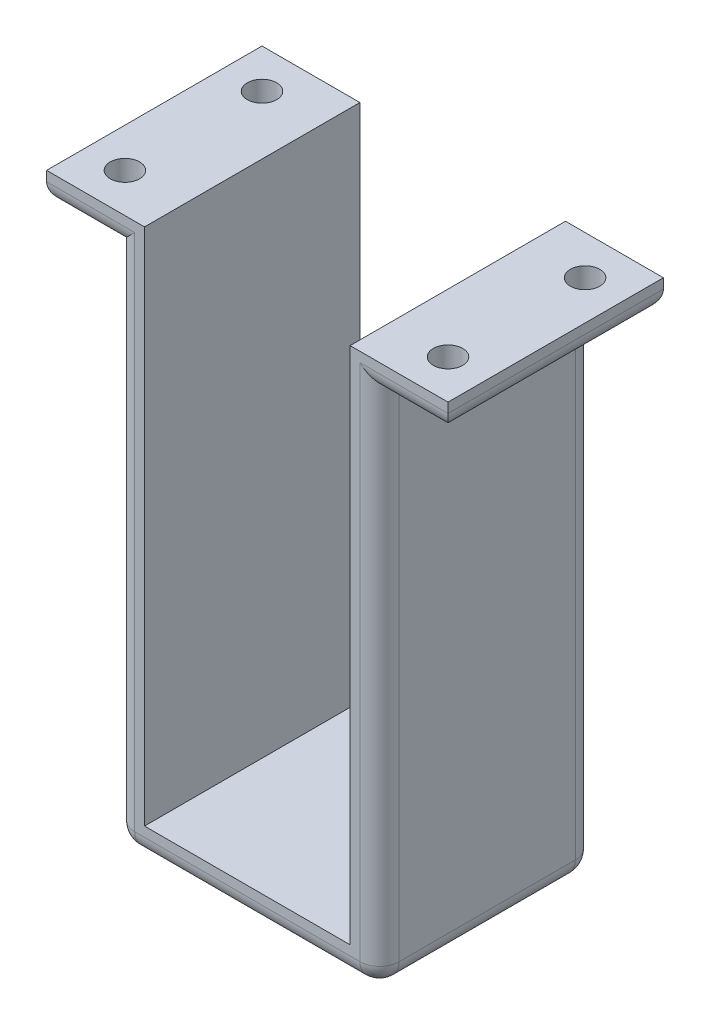
SolidWorks part; units mm, degrees
ref_plane "Alzado" through (0, 0, 0) normal (0, 0, 1) x (1, 0, 0)
ref_plane "Planta" through (0, 0, 0) normal (0, 1, 0) x (1, 0, 0)
ref_plane "Vista lateral" through (0, 0, 0) normal (1, 0, 0) x (0, 0, -1)
sketch "Croquis1" plane through (0, 0, 0) normal (1, 0, 0) x (0, 0, -1)
  line L1 (-22, 0) -> (0, 0)
  line L2 (-22, 0) -> (-22, -50)
  line L3 (-22, -50) -> (0, -50)
  line L4 (0, 0) -> (0, -50)
  dimension "D1" = 50
  dimension "D2" = 22
extrude "Saliente-Extruir2" add sketch "Croquis1" along normal blind 3
sketch "Croquis2" plane through (0, -50, 0) normal (0, -1, 0) x (-1, 0, 0)
  line L0 (-3, -22) -> (-27, -22) construction
  line L2 (0, -22) -> (-27, -22)
  line L3 (0, -22) -> (0, 0)
  line L4 (0, 0) -> (-27, 0)
  line L5 (-27, -22) -> (-27, 0)
  dimension "D1" = 24
  dimension "D2" = 22
extrude "Saliente-Extruir3" add sketch "Croquis2" along normal blind 3
sketch "Croquis3" plane through (0, -50, 0) normal (0, 1, 0) x (1, 0, 0)
  line L0 (27, -22) -> (3, -22) construction
  line L1 (27, 0) -> (24, 0)
  line L2 (27, 0) -> (27, -22)
  line L3 (27, -22) -> (24, -22)
  line L4 (24, 0) -> (24, -22)
  dimension "D1" = 3
extrude "Saliente-Extruir4" add sketch "Croquis3" along normal blind 50
sketch "Croquis4" plane through (0, 0, 0) normal (0, 1, 0) x (1, 0, 0)
  line L1 (3, 0) -> (-7, 0)
  line L2 (3, 0) -> (3, -22)
  line L3 (3, -22) -> (-7, -22)
  line L4 (-7, 0) -> (-7, -22)
  line L5 (24, 0) -> (34, 0)
  line L6 (24, 0) -> (24, -22)
  line L7 (24, -22) -> (34, -22)
  line L8 (34, 0) -> (34, -22)
  circle A0 centre (-3, -4) radius 1.5
  circle A1 centre (-3, -18) radius 1.5
  circle A2 centre (30, -18) radius 1.5
  circle A3 centre (30, -4) radius 1.5
  dimension "D5" = 3
  dimension "D6" = 3
  dimension "D7" = 3
  dimension "D8" = 3
  dimension "D9" = 4
  dimension "D10" = 4
  dimension "D11" = 4
  dimension "D12" = 4
  dimension "D13" = 4
  dimension "D15" = 4
  dimension "D1" = 10
  dimension "D2" = 22
  dimension "D3" = 10
  dimension "D4" = 22
  dimension "D14" = 4
  dimension "D16" = 4
extrude "Saliente-Extruir5" add sketch "Croquis4" along normal blind 3
fillet "Redondeo1" radius 2 14 edges at (13.5, -53, 0) (13.5, -53, 22) (-3.5, 0, 0) (-7, 0, 11) (-3.5, 0, 22) (0, -53, 11) (0, -26.5, 0) (0, -26.5, 22) (27, -53, 11) (27, -26.5, 22) (27, -26.5, 0) (30.5, 0, 0) (30.5, 0, 22) (34, 0, 11)
